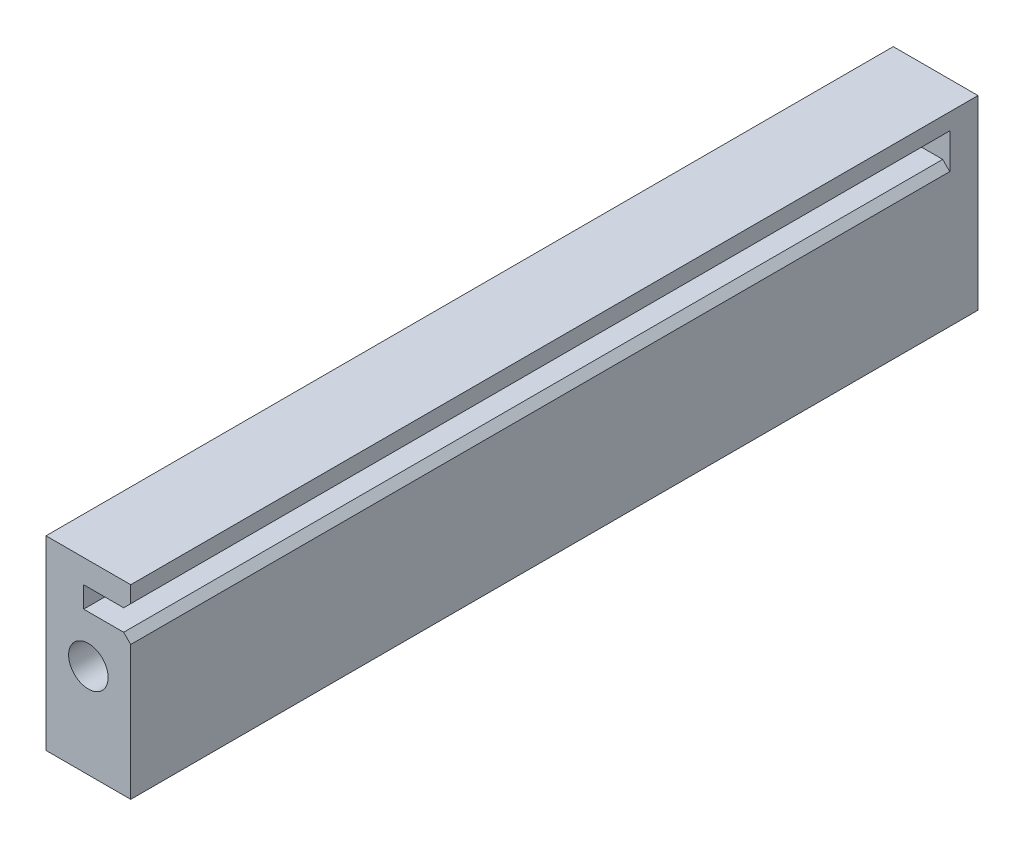
SolidWorks part; units mm, degrees
ref_plane "Спереди" through (0, 0, 0) normal (0, 0, 1) x (1, 0, 0)
ref_plane "Сверху" through (0, 0, 0) normal (0, 1, 0) x (1, 0, 0)
ref_plane "Справа" through (0, 0, 0) normal (1, 0, 0) x (0, 0, -1)
sketch "Эскиз1" plane through (0, 0, 0) normal (0, 0, 1) x (1, 0, 0)
  line L1 (-4.5, -7.5) -> (4.5, -7.5)
  line L2 (-4.5, -7.5) -> (-4.5, 7.5)
  line L3 (-4.5, 7.5) -> (4.5, 7.5)
  line L4 (4.5, -7.5) -> (4.5, 7.5)
  line L5 (-4.5, -7.5) -> (4.5, 7.5) construction
  line L6 (-4.5, 7.5) -> (4.5, -7.5) construction
  line L7 (-4.5, 7.5) -> (4.5, 7.5)
  line L8 (-4.5, 7.5) -> (-4.5, 12.25)
  line L9 (-4.5, 12.25) -> (4.5, 12.25)
  line L10 (4.5, 7.5) -> (4.5, 12.25)
  line L11 (4.5, 7.5) -> (-0.5, 7.5)
  line L12 (4.5, 7.5) -> (4.5, 9.75)
  line L13 (4.5, 9.75) -> (-0.5, 9.75)
  line L14 (-0.5, 7.5) -> (-0.5, 9.75)
  point P0 (0, 0)
  dimension "D1" = 9
  dimension "D2" = 15
  dimension "D3" = 2.25
  dimension "D4" = 2.5
  dimension "D5" = 4
extrude "Бобышка-Вытянуть1" add sketch "Эскиз1" along normal blind 90 contours L1 L4 L7 L3 L2 | L3 L14 L13 L10 L9 L8
sketch "Эскиз2" plane through (0, -7.5, 0) normal (0, -1, 0) x (1, 0, 0)
  line L0 (0, 90) -> (0, 67.5) construction
  line L1 (-4.5, 90) -> (4.5, 90) construction
  line L2 (0, 67.5) -> (0, 45) construction
  line L3 (0, 22.5) -> (0, 0) construction
  line L4 (-4.5, 0) -> (4.5, 0) construction
  line L5 (0, 45) -> (0, 22.5) construction
  circle A0 centre (0, 22.5) radius 2.1
  circle A1 centre (0, 67.5) radius 2.1
  circle A2 centre (0, 45) radius 2.1
  dimension "D1" = 4.2
extrude "Вырез-Вытянуть1" cut sketch "Эскиз2" against normal blind 6
sketch "Эскиз3" plane through (0, 0, 0) normal (0, 0, -1) x (-1, 0, 0)
  line L1 (-4.5, 9.75) -> (0.5, 9.75)
  line L2 (-4.5, 9.75) -> (-4.5, 7.5)
  line L3 (-4.5, 7.5) -> (0.5, 7.5)
  line L4 (0.5, 9.75) -> (0.5, 7.5)
extrude "Бобышка-Вытянуть2" add sketch "Эскиз3" against normal blind 3
chamfer "Фаска1" distance 0.75 angle 45 2 edges at (4.5, 7.5, 46.5) (4.5, 9.75, 46.5)
sketch "Эскиз4" plane through (0, 0, 90) normal (0, 0, 1) x (1, 0, 0)
  line L0 (-4.5, -7.5) -> (4.5, -7.5) construction
  circle A0 centre (0, 2.5) radius 2.1
  dimension "D1" = 4.2
  dimension "D2" = 10
extrude "Вырез-Вытянуть2" cut sketch "Эскиз4" against normal blind 6
